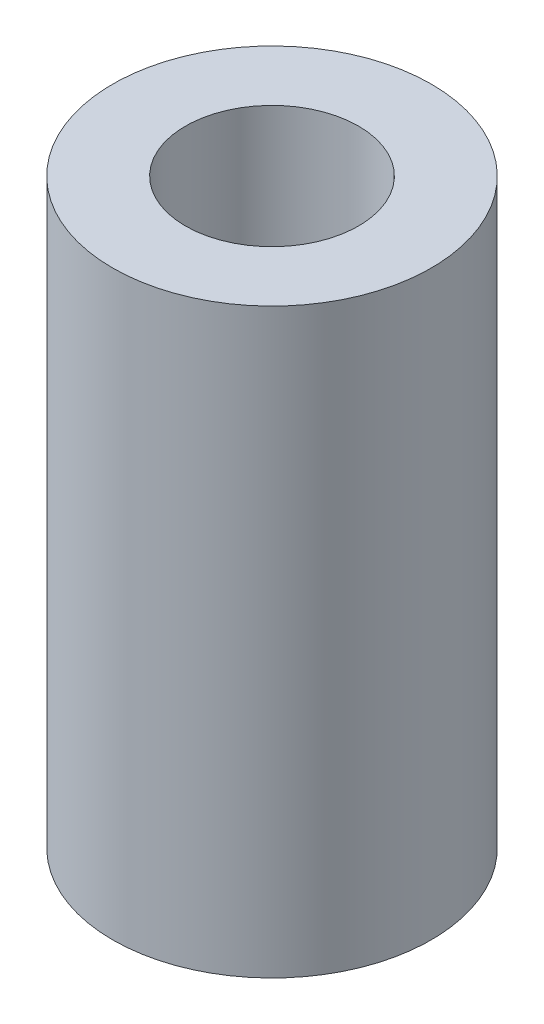
SolidWorks part; units mm, degrees
ref_plane "Front Plane" through (0, 0, 0) normal (0, 0, 1) x (1, 0, 0)
ref_plane "Top Plane" through (0, 0, 0) normal (0, 1, 0) x (1, 0, 0)
ref_plane "Right Plane" through (0, 0, 0) normal (1, 0, 0) x (0, 0, -1)
sketch "Sketch1" plane through (0, 0, 0) normal (0, 1, 0) x (1, 0, 0)
  circle A0 centre (0, 0) radius 2.0828
  circle A1 centre (0, 0) radius 3.8328
  dimension "D1" = 1.75
  dimension "D2" = 4.1656
extrude "Boss-Extrude1" add sketch "Sketch1" along normal blind 14
ref_plane "Plane1" through (0, 7, 0) normal (0, 1, 0) x (1, 0, 0)
